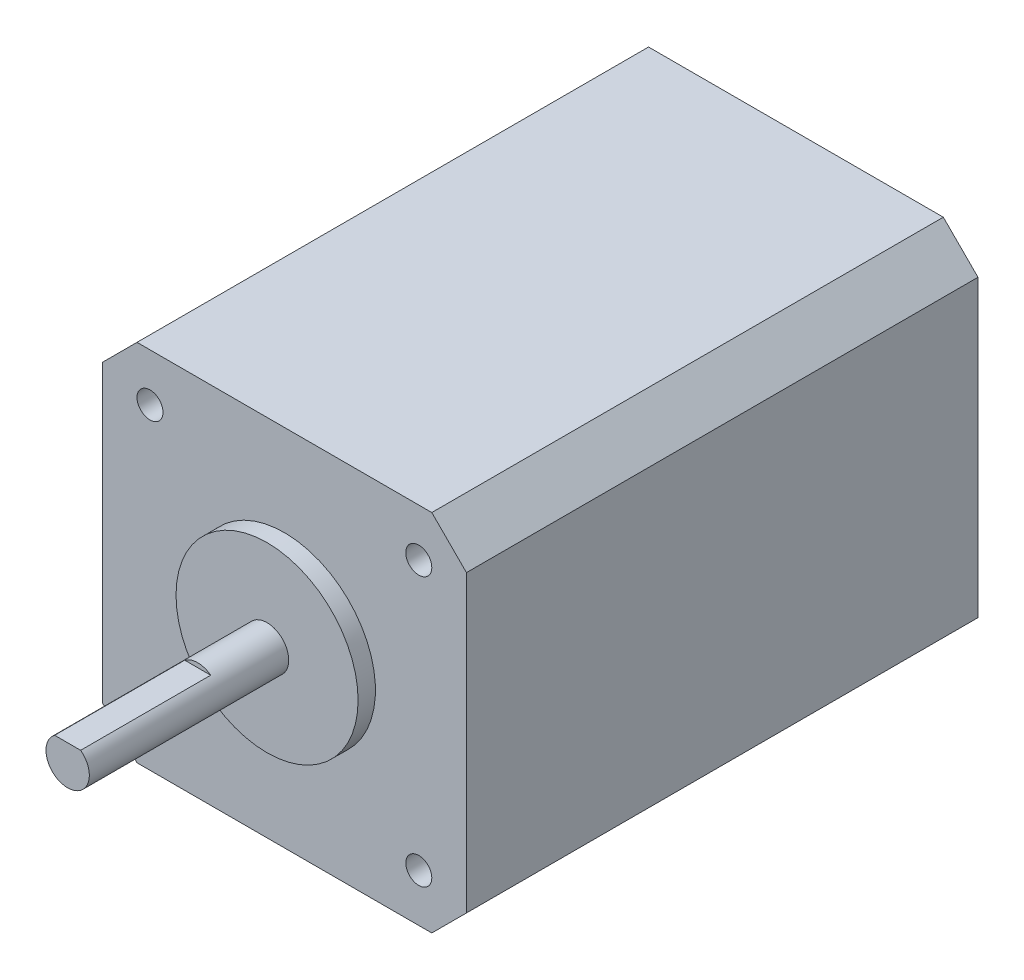
SolidWorks part; units mm, degrees
ref_plane "Ebene vorne" through (0, 0, 0) normal (0, 0, 1) x (1, 0, 0)
ref_plane "Ebene oben" through (0, 0, 0) normal (0, 1, 0) x (1, 0, 0)
ref_plane "Ebene rechts" through (0, 0, 0) normal (1, 0, 0) x (0, 0, -1)
sketch "Skizze1" plane through (0, 0, 0) normal (0, 0, 1) x (1, 0, 0)
  line L0 (15.5, 15.5) -> (15.5, -15.5) construction
  line L1 (-17, -21) -> (17, -21)
  line L2 (-21, -17) -> (-21, 17)
  line L3 (-17, 21) -> (17, 21)
  line L4 (21, -17) -> (21, 17)
  line L5 (-21, -21) -> (21, 21) construction
  line L6 (-21, 21) -> (21, -21) construction
  line L7 (-21, 17) -> (-17, 21)
  line L8 (17, 21) -> (21, 17)
  line L9 (17, -21) -> (21, -17)
  line L10 (-21, -17) -> (-17, -21)
  circle A0 centre (15.5, 15.5) radius 1.5
  circle A1 centre (15.5, -15.5) radius 1.5
  circle A2 centre (-15.5, -15.5) radius 1.5
  circle A3 centre (-15.5, 15.5) radius 1.5
  point P0 (0, 0)
  point P18 (0, 0)
  dimension "D3" = 4
  dimension "D1" = 42
  dimension "D2" = 42
extrude "Aufsatz-Linear austragen1" add sketch "Skizze1" along normal blind 59
sketch "Skizze2" plane through (0, 0, 59) normal (0, 0, 1) x (1, 0, 0)
  circle A0 centre (0, 0) radius 10.5
  dimension "D1" = 21
extrude "Aufsatz-Linear austragen2" add sketch "Skizze2" along normal blind 2
sketch "Skizze3" plane through (0, 0, 61) normal (0, 0, 1) x (1, 0, 0)
  circle A0 centre (0, 0) radius 2.5
  dimension "D1" = 5
extrude "Aufsatz-Linear austragen3" add sketch "Skizze3" along normal blind 23
sketch "Skizze4" plane through (0, 0, 84) normal (0, 0, 1) x (1, 0, 0)
  line L0 (-1.5, 2) -> (1.5, 2)
  circle A0 centre (0, 0) radius 2.5
  circle M2 centre (0, 0) radius 2.5
  dimension "D2" = 5
  dimension "D1" = 3
extrude "Schnitt-Linear austragen1" cut sketch "Skizze4" against normal blind 15 contours L0 M2
